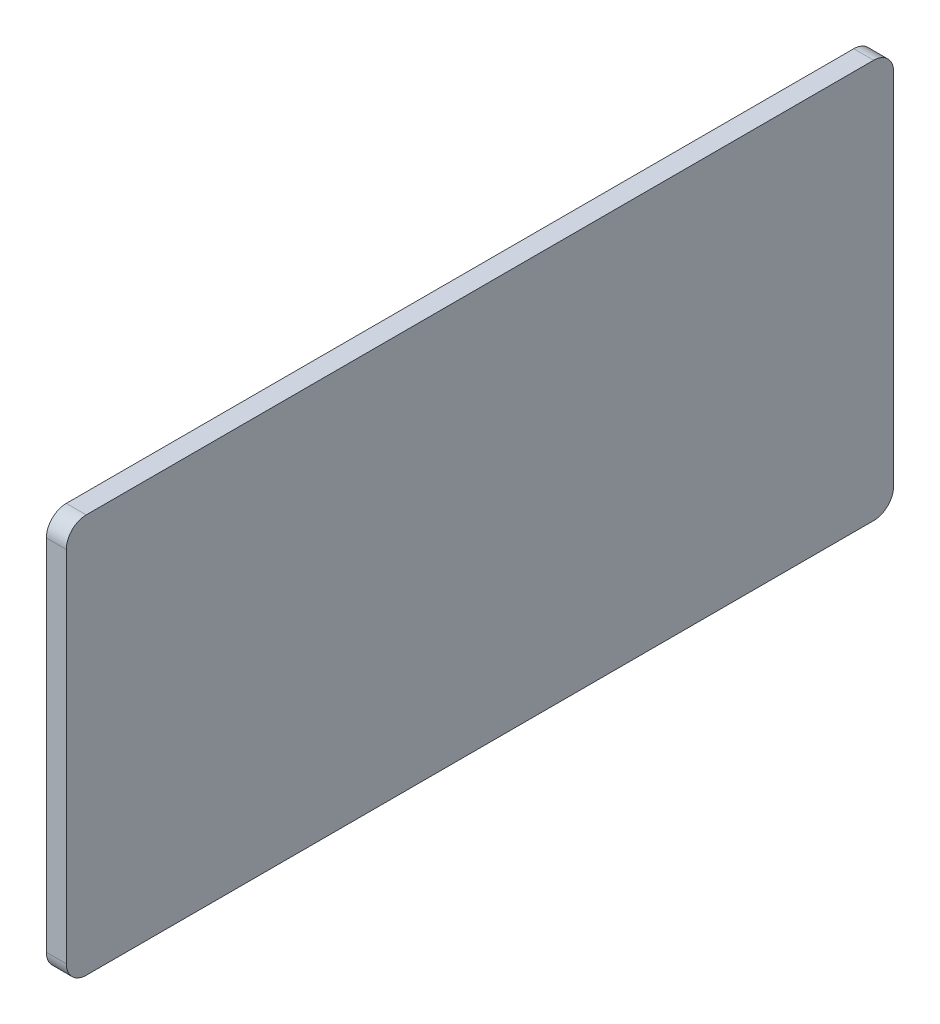
SolidWorks part; units mm, degrees
ref_plane "Plan de face" through (0, 0, 0) normal (0, 0, 1) x (1, 0, 0)
ref_plane "Plan de dessus" through (0, 0, 0) normal (0, 1, 0) x (1, 0, 0)
ref_plane "Plan de droite" through (0, 0, 0) normal (1, 0, 0) x (0, 0, -1)
sketch "Esquisse1" plane through (0, 0, 0) normal (1, 0, 0) x (0, 0, -1)
  line L1 (39.5, -20) -> (-39.5, -20)
  line L2 (41.5, -18) -> (41.5, 18)
  line L3 (39.5, 20) -> (-39.5, 20)
  line L4 (-41.5, -18) -> (-41.5, 18)
  line L5 (41.5, -20) -> (-41.5, 20) construction
  line L6 (41.5, 20) -> (-41.5, -20) construction
  arc A0 (-39.5, -20) -> (-41.5, -18) centre (-39.5, -18) cw
  arc A1 (39.5, -20) -> (41.5, -18) centre (39.5, -18) ccw
  arc A2 (41.5, 18) -> (39.5, 20) centre (39.5, 18) ccw
  arc A3 (-39.5, 20) -> (-41.5, 18) centre (-39.5, 18) ccw
  point P0 (0, 0)
  dimension "D3" = 2
  dimension "D1" = 83
  dimension "D2" = 40
extrude "Boss.-Extru.1" add sketch "Esquisse1" along normal blind 2
